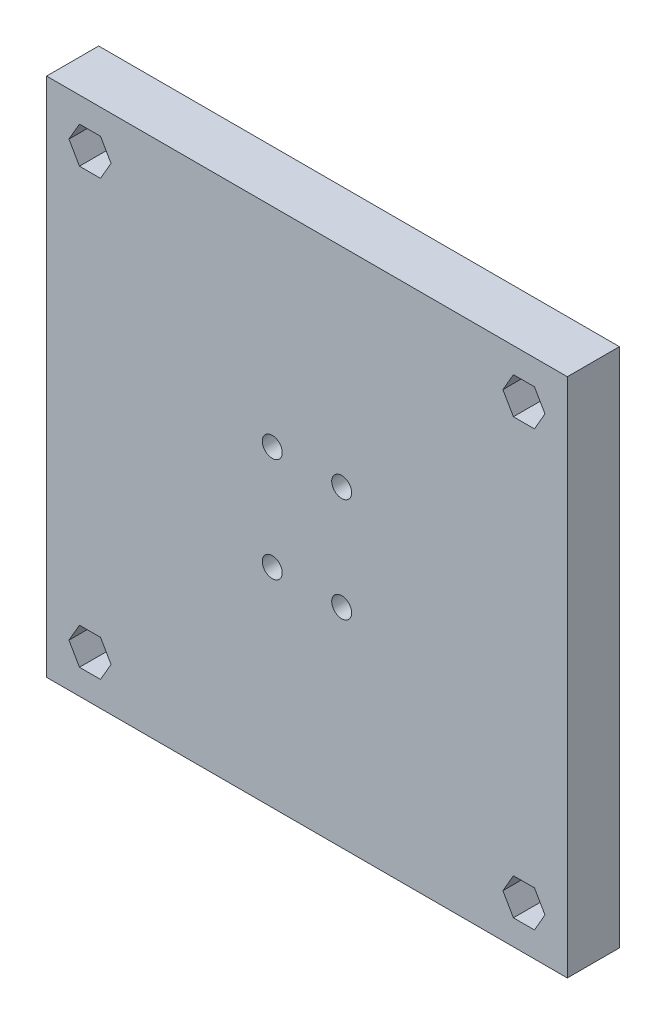
SolidWorks part; units mm, degrees
ref_plane "Front Plane" through (0, 0, 0) normal (0, 0, 1) x (1, 0, 0)
ref_plane "Top Plane" through (0, 0, 0) normal (0, 1, 0) x (1, 0, 0)
ref_plane "Right Plane" through (0, 0, 0) normal (1, 0, 0) x (0, 0, -1)
sketch "Sketch1" plane through (0, 0, 0) normal (0, 0, 1) x (1, 0, 0)
  line L1 (-30, 30) -> (30, 30)
  line L2 (-30, 30) -> (-30, -30)
  line L3 (-30, -30) -> (30, -30)
  line L4 (30, 30) -> (30, -30)
  line L5 (-30, 30) -> (30, -30) construction
  line L6 (-30, -30) -> (30, 30) construction
  point P0 (0, 0)
  dimension "D1" = 60
  dimension "D2" = 60
extrude "Boss-Extrude1" add sketch "Sketch1" along normal blind 6
sketch "Sketch2" plane through (0, 0, 6) normal (0, 0, 1) x (1, 0, 0)
  line L0 (-25, 20) -> (-25, 30)
  line L1 (-30, 30) -> (-20, 30)
  line L2 (-30, 30) -> (-30, 20)
  line L3 (-30, 20) -> (-20, 20)
  line L4 (-20, 30) -> (-20, 20)
  circle A0 centre (-25, 25) radius 1.15
  circle A1 centre (25, 25) radius 1.15
  circle A2 centre (25, -25) radius 1.15
  circle A3 centre (-25, -25) radius 1.15
  point P9 (0, 0)
  point P20 (0, 0)
  dimension "D3" = 2.3
  dimension "D1" = 10
  dimension "D2" = 10
  dimension "D4" = 4
extrude "Cut-Extrude1" cut sketch "Sketch2" against normal through all contours L0 A0 | L0 A0 | A1 | A2 | A3
sketch "Sketch3" plane through (0, 0, 6) normal (0, 0, 1) x (1, 0, 0)
  line L0 (0, 0) -> (24.9087, 0)
  line L1 (-22.5751, 25) -> (-23.7876, 27.1)
  line L2 (-23.7876, 27.1) -> (-26.2124, 27.1)
  line L3 (-26.2124, 27.1) -> (-27.4249, 25)
  line L4 (-27.4249, 25) -> (-26.2124, 22.9)
  line L5 (-26.2124, 22.9) -> (-23.7876, 22.9)
  line L6 (-23.7876, 22.9) -> (-22.5751, 25)
  line L7 (0, 0) -> (0, 14.5359)
  line L8 (23.7876, 22.9) -> (22.5751, 25)
  line L9 (26.2124, 22.9) -> (23.7876, 22.9)
  line L10 (27.4249, 25) -> (26.2124, 22.9)
  line L11 (26.2124, 27.1) -> (27.4249, 25)
  line L12 (23.7876, 27.1) -> (26.2124, 27.1)
  line L13 (22.5751, 25) -> (23.7876, 27.1)
  line L14 (26.2124, -22.9) -> (23.7876, -22.9)
  line L15 (27.4249, -25) -> (26.2124, -22.9)
  line L16 (26.2124, -27.1) -> (27.4249, -25)
  line L17 (23.7876, -27.1) -> (26.2124, -27.1)
  line L18 (22.5751, -25) -> (23.7876, -27.1)
  line L19 (23.7876, -22.9) -> (22.5751, -25)
  line L20 (-23.7876, -22.9) -> (-22.5751, -25)
  line L21 (-26.2124, -22.9) -> (-23.7876, -22.9)
  line L22 (-27.4249, -25) -> (-26.2124, -22.9)
  line L23 (-26.2124, -27.1) -> (-27.4249, -25)
  line L24 (-23.7876, -27.1) -> (-26.2124, -27.1)
  line L25 (-22.5751, -25) -> (-23.7876, -27.1)
  circle A0 centre (-25, 25) radius 2.1 construction
  circle M15 centre (-25, -25) radius 1.15
  circle M16 centre (25, -25) radius 1.15
  circle M17 centre (25, 25) radius 1.15
  circle M18 centre (-25, 25) radius 1.15
extrude "Cut-Extrude2" cut sketch "Sketch3" against normal blind 4 contours L5 L6 L1 L2 L3 L4 M18 | L13 L8 L9 L10 L11 L12 M17 | L14 L19 L18 L17 L16 L15 M16 | L25 L20 L21 L22 L23 L24 M15
sketch "Sketch4" plane through (0, 0, 0) normal (0, 0, -1) x (-1, 0, 0)
  line L0 (0, 30) -> (0, -30)
  line L1 (-30, 30) -> (30, 30) construction
  line L2 (30, -30) -> (-30, -30) construction
  line L3 (0, 0) -> (4, 0)
  line L4 (-4, -6) -> (4, -6)
  line L5 (-4, -6) -> (-4, 6)
  line L6 (-4, 6) -> (4, 6)
  line L7 (4, -6) -> (4, 6)
  line L8 (-4, -6) -> (4, 6) construction
  line L9 (-4, 6) -> (4, -6) construction
  circle A0 centre (-4, 6) radius 2.1
  circle A1 centre (-4, -6) radius 2.1
  circle A2 centre (4, -6) radius 2.1
  circle A3 centre (4, 6) radius 2.1
  point P6 (0, 0)
  dimension "D1" = 8
  dimension "D2" = 12
extrude "Cut-Extrude3" cut sketch "Sketch4" against normal blind 3 contours L6 A0 L5 | L5 A0 L6 | A3 L6 L7 | A3 L7 L6 | L4 A2 L7 | L7 A2 L4 | A1 L4 L5 | A1 L5 L4
sketch "Sketch5" plane through (0, 0, 3) normal (0, 0, -1) x (-1, 0, 0)
  line L0 (0, 0) -> (0, 7.6334)
  line L1 (0, 0) -> (3.7999, 0)
  circle A0 centre (-4, 6) radius 1.15
  circle A1 centre (4, 6) radius 1.15
  circle A2 centre (4, -6) radius 1.15
  circle A3 centre (-4, -6) radius 1.15
extrude "Cut-Extrude4" cut sketch "Sketch5" against normal through all contours A0 | A1 | A2 | A3
